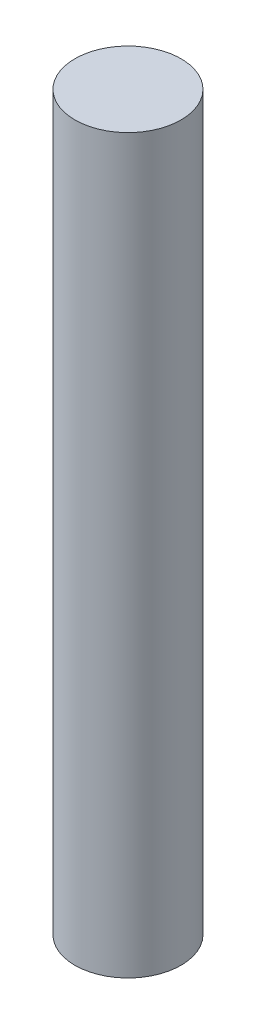
SolidWorks part; units mm, degrees
ref_plane "前视基准面" through (0, 0, 0) normal (0, 0, 1) x (1, 0, 0)
ref_plane "上视基准面" through (0, 0, 0) normal (0, 1, 0) x (1, 0, 0)
ref_plane "右视基准面" through (0, 0, 0) normal (1, 0, 0) x (0, 0, -1)
sketch "草图1" plane through (0, 0, 0) normal (0, 1, 0) x (1, 0, 0)
  circle A0 centre (0, 0) radius 5
  dimension "D1" = 10
extrude "凸台-拉伸1" add sketch "草图1" along normal blind 69
